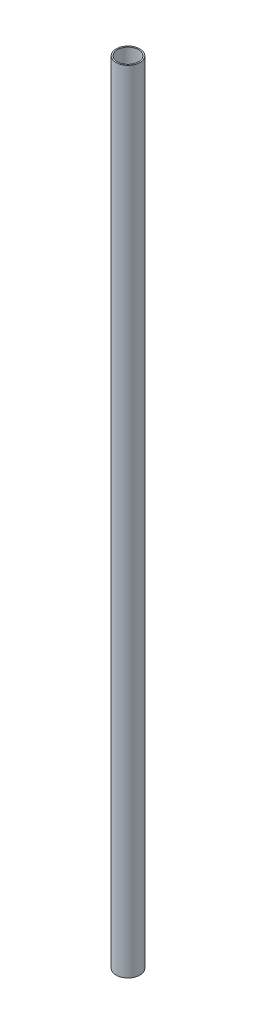
SolidWorks part; units mm, degrees
material "6061-T6 (SS)"
ref_plane "Front Plane" through (0, 0, 0) normal (0, 0, 1) x (1, 0, 0)
ref_plane "Top Plane" through (0, 0, 0) normal (0, 1, 0) x (1, 0, 0)
ref_plane "Right Plane" through (0, 0, 0) normal (1, 0, 0) x (0, 0, -1)
sketch "Sketch2" plane through (0, 0, 0) normal (0, 1, 0) x (1, 0, 0)
  circle A0 centre (0, 0) radius 7.9375
  circle A1 centre (0, 0) radius 7.0485
  dimension "D1" = 15.875
  dimension "D2" = 0.889
extrude "Boss-Extrude1" add sketch "Sketch2" along normal blind 527.05
